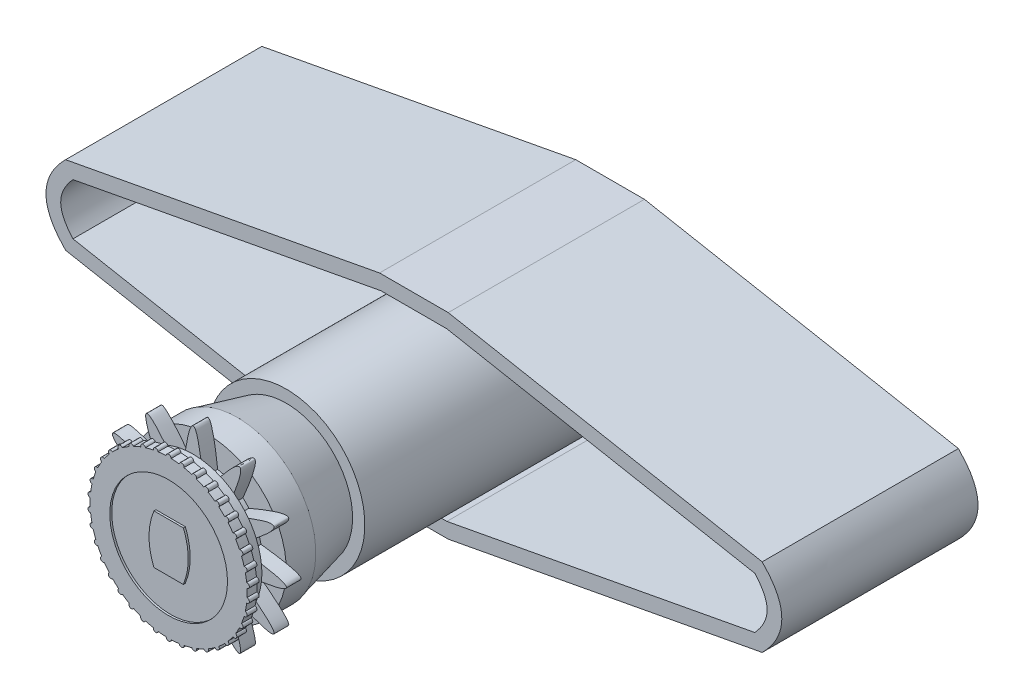
SolidWorks part; units mm, degrees
ref_plane "Front Plane" through (0, 0, 0) normal (0, 0, 1) x (1, 0, 0)
ref_plane "Top Plane" through (0, 0, 0) normal (0, 1, 0) x (1, 0, 0)
ref_plane "Right Plane" through (0, 0, 0) normal (1, 0, 0) x (0, 0, -1)
sketch "Sketch1" plane through (0, 0, 0) normal (0, 0, 1) x (1, 0, 0)
  circle A0 centre (0, 0) radius 5.5
  dimension "D1" = 11
extrude "Boss-Extrude1" add sketch "Sketch1" along normal blind 1.5
sketch "Sketch2" plane through (0, 0, 1.5) normal (0, 0, 1) x (1, 0, 0)
  line L0 (0, 0) -> (0, 10.5863) construction
  line L1 (0, 5.5) -> (0, 9.4083) construction
  line L2 (-1, 9.5) -> (1, 9.5) construction
  line L3 (-1, 9.5) -> (-1, 5.4083) construction
  line L4 (-1, 5.4083) -> (1, 5.4083) construction
  line L5 (1, 9.5) -> (1, 5.4083) construction
  line L6 (-1, 9.5) -> (1, 5.4083) construction
  line L7 (-1, 5.4083) -> (1, 9.5) construction
  line L10 (-1, 5.4083) -> (1, 5.4083)
  circle A0 centre (0, 0) radius 5.5 construction
  spline S0 degree 2 poles (-1, 5.4083) (0, 13.5917) (1, 5.4083) knots 0 0 0 1 1 1
  point P0 (0, 7.4542)
  point P7 (0, 7.4542)
  point P11 (-0.7667, 9.5)
  point P12 (0.2333, 9.5)
extrude "Boss-Extrude3" add sketch "Sketch2" against normal blind 1.5
pattern_circular "CirPattern2" count 12 over 360 about axis through (0, 0, 1.5) along (0, 0, -1) of "Boss-Extrude3"
sketch "Sketch3" plane through (0, 0, 1.5) normal (0, 0, 1) x (1, 0, 0)
  circle A0 centre (0, 0) radius 7
  dimension "D1" = 14
extrude "Boss-Extrude4" add sketch "Sketch3" along normal blind 1.5
sketch "Sketch4" plane through (0, 0, 3) normal (0, 0, 1) x (1, 0, 0)
  circle A0 centre (0, 0) radius 8
  dimension "D1" = 16
extrude "Boss-Extrude5" add sketch "Sketch4" along normal blind 1
sketch "Sketch6" plane through (0, 0, 4) normal (0, 0, 1) x (1, 0, 0)
  line L0 (0, 0) -> (0, 10.621) construction
  circle A0 centre (0, 8) radius 0.25
  circle A1 centre (0, 0) radius 8 construction
  dimension "D1" = 0.5
extrude "Boss-Extrude7" add sketch "Sketch6" against normal blind 1
pattern_circular "CirPattern3" count 38 over 360 about axis through (0, 0, 0) along (0, 0, 1) of "Boss-Extrude7"
sketch "Sketch7" plane through (0, 0, 4) normal (0, 0, 1) x (1, 0, 0)
  circle A0 centre (0, 0) radius 6
extrude "Cut-Extrude1" cut sketch "Sketch7" against normal blind 0.2
sketch "Sketch8" plane through (0, 0, 3.8) normal (0, 0, 1) x (1, 0, 0)
  line L0 (-1.5, -2.5) -> (1.5, -2.5)
  line L8 (2, 2) -> (2.0184, 1.9675) construction
  line L11 (-1.5, 2.5) -> (1.5, 2.5)
  spline S0 degree 2 poles (-1.5, 2.5) (-2.5, 0) (-1.5, -2.5) knots 0 0 0 1 1 1
  spline S2 degree 2 poles (1.5, 2.5) (2.5, 0) (1.5, -2.5) knots 0 0 0 1 1 1
  point P0 (0, 0)
  point P10 (-1.5, 2.5)
  point P11 (1.5, 2.5)
  point P12 (-1.5, -2.5)
  point P13 (1.5, -2.5)
  point P14 (-6.1413, 10.3588)
extrude "Boss-Extrude9" add sketch "Sketch8" along normal blind 0.2
sketch "Sketch10" plane through (0, 0, 0) normal (0, 0, -1) x (-1, 0, 0)
  circle A0 centre (0, 0) radius 8
  dimension "D1" = 16
extrude "Boss-Extrude10" add sketch "Sketch10" along normal blind 3
ref_plane "Plane1" through (0, 0, -8) normal (0, 0, -1) x (-1, 0, 0)
sketch "Sketch11" plane through (0, 0, -8) normal (0, 0, -1) x (-1, 0, 0)
  circle A0 centre (0, 0) radius 6.75
  dimension "D1" = 13.5
extrude "Boss-Extrude11" add sketch "Sketch11" against normal up to surface (5 mm away) draft 13.7
sketch "Sketch12" plane through (0, 0, -8) normal (0, 0, -1) x (-1, 0, 0)
  circle A0 centre (0, 0) radius 8
  dimension "D1" = 16
extrude "Boss-Extrude12" add sketch "Sketch12" along normal blind 33
ref_plane "Plane2" through (0, 0, -41) normal (0, 0, -1) x (-1, 0, 0)
sketch "Sketch13" plane through (0, 0, -41) normal (0, 0, -1) x (-1, 0, 0)
  line L0 (37.5013, -0.0003) -> (-37.4987, -0.0003) construction
  line L1 (-37.4987, 9.9997) -> (37.5013, 9.9997) construction
  line L2 (-37.4987, 9.9997) -> (-37.4987, -10.0003) construction
  line L3 (-37.4987, -10.0003) -> (37.5013, -10.0003) construction
  line L4 (37.5013, 9.9997) -> (37.5013, -10.0003) construction
  line L5 (-37.4987, 9.9997) -> (37.5013, -10.0003) construction
  line L6 (-37.4987, -10.0003) -> (37.5013, 9.9997) construction
  line L7 (0.0013, 9.9997) -> (0.0013, -10.0003) construction
  line L8 (0.0013, -10.0003) -> (-0.242, -10.2388) construction
  line L9 (3.5013, 9.9997) -> (3.5013, -10.0003) construction
  line L10 (-37.4987, 3.9997) -> (37.5013, 3.9997) construction
  line L11 (37.5013, -4.0003) -> (-37.4987, -4.0003) construction
  line L12 (3.5013, -10.0003) -> (3.293, -10.1261) construction
  line L13 (-3.4987, 9.9997) -> (-3.4987, -10.0003) construction
  line L14 (-35.4987, 9.9997) -> (-35.4987, -10.0003) construction
  line L15 (35.5013, 9.9997) -> (35.5013, -10.0003) construction
  line L16 (-35.4987, 3.9997) -> (-3.4987, 9.9997)
  line L17 (-3.4987, 9.9997) -> (3.5013, 9.9997)
  line L18 (3.5013, 9.9997) -> (35.5013, 3.9997)
  line L19 (35.5013, -4.0003) -> (3.5013, -10.0003)
  line L20 (3.5013, -10.0003) -> (-3.4987, -10.0003)
  line L21 (-3.4987, -10.0003) -> (-35.4987, -4.0003)
  spline S0 degree 2 poles (-35.4987, 3.9997) (-39.4987, -0.0003) (-35.4987, -4.0003) knots 0 0 0 1 1 1
  spline S1 degree 2 poles (35.5013, 3.9997) (39.5013, -0.0003) (35.5013, -4.0003) knots 0 0 0 1 1 1
  point P0 (0.0013, -0.0003)
  point P8 (37.5013, -8.5003)
  point P9 (37.5013, 3.9997)
  point P10 (37.5013, -4.0003)
  point P22 (-3.4987, 9.9997)
  point P23 (3.5013, 9.9997)
  dimension "D1" = 2
  dimension "D2" = 2
extrude "Boss-Extrude13" add sketch "Sketch13" against normal blind 20 separate body
shell "Shell1" thickness 1.5
